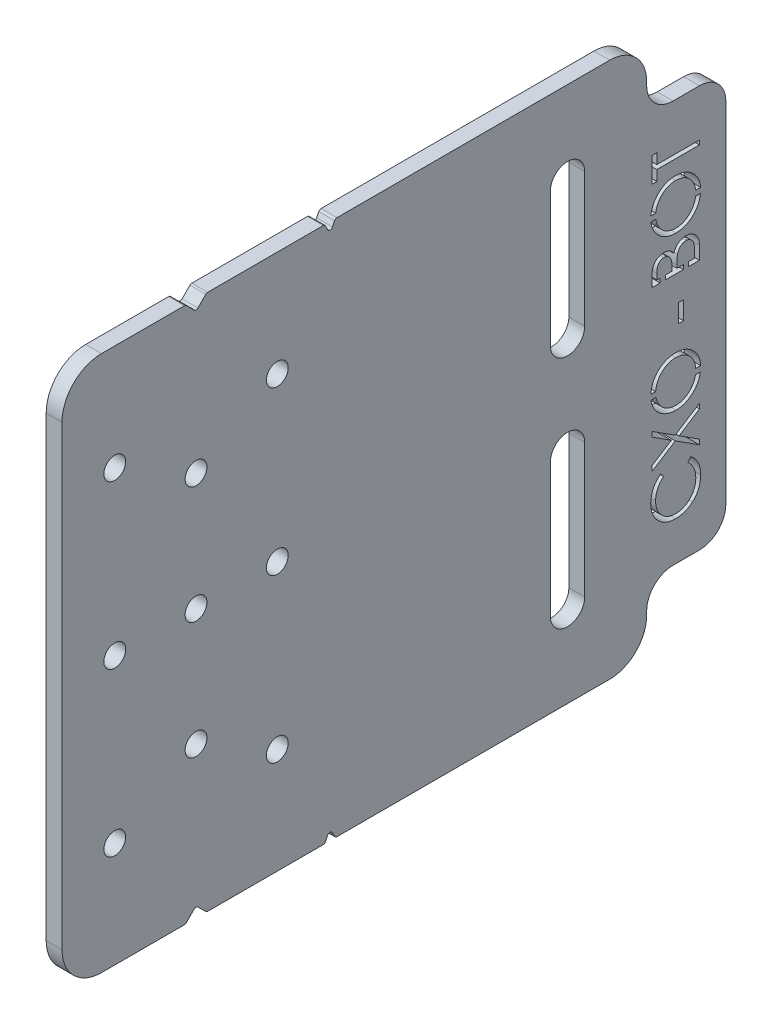
SolidWorks part; units mm, degrees
ref_plane "Front Plane" through (0, 0, 0) normal (0, 0, 1) x (1, 0, 0)
ref_plane "Top Plane" through (0, 0, 0) normal (0, 1, 0) x (1, 0, 0)
ref_plane "Right Plane" through (0, 0, 0) normal (1, 0, 0) x (0, 0, -1)
sketch "Sketch1" plane through (0, 0, 0) normal (1, 0, 0) x (0, 0, -1)
  line L0 (25.4, 60.8724) -> (25.4, -43.1362) construction
  line L1 (0, 55) -> (0, -55) construction
  line L2 (-25.4, 60.8724) -> (-25.4, -43.1362) construction
  line L3 (70.4, 39.6984) -> (70.4, -31.2158) construction
  line L4 (-25.4, 50.8) -> (25.4, 50.8)
  line L5 (-25.4, 50.8) -> (-25.4, -50.8)
  line L6 (-25.4, -50.8) -> (25.4, -50.8)
  line L7 (25.4, 50.8) -> (25.4, -50.8)
  line L8 (-25.4, 50.8) -> (25.4, -50.8) construction
  line L9 (-25.4, -50.8) -> (25.4, 50.8) construction
  line L10 (70.4, 34.925) -> (70.4, 9.525) construction
  line L11 (73.65, 34.925) -> (73.65, 9.525)
  line L12 (67.15, 34.925) -> (67.15, 9.525)
  line L13 (70.4, -9.525) -> (70.4, -34.925) construction
  line L14 (73.65, -9.525) -> (73.65, -34.925)
  line L15 (67.15, -9.525) -> (67.15, -34.925)
  line L16 (0, 22.225) -> (0, -22.225) construction
  line L17 (85.4, 58.462) -> (85.4, -44.2534) construction
  line L18 (55.4, 58.462) -> (55.4, -44.2534) construction
  line L19 (25.4, 50.8) -> (85.4, 50.8)
  line L20 (85.4, 50.8) -> (85.4, -50.8)
  line L21 (85.4, -50.8) -> (25.4, -50.8)
  line L22 (0, 0) -> (-25.4, 0) construction
  line L23 (-15.4, 30.8) -> (-15.4, 0) construction
  line L24 (-15.4, 15.4) -> (-25.4, 15.4) construction
  line L25 (-2, 50.8) -> (0, 48.8)
  line L26 (0, 48.8) -> (2, 50.8)
  line L27 (-2, -50.8) -> (0, -48.8)
  line L28 (0, -48.8) -> (2, -50.8)
  line L29 (24.4, 50.8) -> (25.4, 48.8)
  line L30 (25.4, 48.8) -> (26.4, 50.8)
  line L31 (24.4, -50.8) -> (25.4, -48.8)
  line L32 (25.4, -48.8) -> (26.4, -50.8)
  arc A0 (73.65, 34.925) -> (67.15, 34.925) centre (70.4, 34.925) ccw
  arc A1 (67.15, 9.525) -> (73.65, 9.525) centre (70.4, 9.525) ccw
  arc A2 (73.65, -9.525) -> (67.15, -9.525) centre (70.4, -9.525) ccw
  arc A3 (67.15, -34.925) -> (73.65, -34.925) centre (70.4, -34.925) ccw
  circle A4 centre (0, 22.225) radius 2.07
  circle A5 centre (0, -22.225) radius 2.07
  circle A7 centre (15.4, 30.8) radius 2.07
  circle A8 centre (15.4, -30.8) radius 2.07
  circle A9 centre (-15.4, -30.8) radius 2.07
  circle A10 centre (-15.4, 30.8) radius 2.07
  circle A11 centre (0, 0) radius 2.07
  circle A12 centre (15.4, 0) radius 2.07
  circle A13 centre (-15.4, 0) radius 2.07
  point P8 (0, 0)
  point P17 (70.4, 22.225)
  point P22 (70.4, -22.225)
  point P30 (0, 0)
  dimension "D10" = 4.14
  dimension "D12" = 2
  dimension "D1" = 25.4
  dimension "D2" = 50.8
  dimension "D3" = 30
  dimension "D4" = 6.5
  dimension "D5" = 25.4
  dimension "D6" = 50.8
  dimension "D7" = 101.6
  dimension "D8" = 19.05
  dimension "D9" = 15
  dimension "D11" = 10
  dimension "D13" = 1
extrude "Boss-Extrude1" add sketch "Sketch1" along normal mid plane 3 contours L21 L20 L19 L7 A3 L15 A2 L14 A1 L12 A0 L11 | L7 L4 L5 L6
fillet "Fillet1" radius 7.5 2 edges at (0, -50.8, 25.4) (0, 50.8, 25.4)
fillet "Fillet2" radius 0.5 12 edges at (0, -50.8, -24.4) (0, -48.8, -25.4) (0, -50.8, -26.4) (0, -50.8, 2) (0, -50.8, -2) (0, -48.8, 0) (0, 50.8, -24.4) (0, 50.8, -26.4) (0, 48.8, 0) (0, 48.8, -25.4) (0, 50.8, -2) (0, 50.8, 2)
fillet "Fillet3" radius 7 2 edges at (0, 50.8, -85.4) (0, -50.8, -85.4)
sketch "Sketch2" plane through (1.5, 0, 0) normal (1, 0, 0) x (0, 0, -1)
  line L0 (100.4, 38.1) -> (100.4, -38.1)
  line L1 (26.709, 50.8) -> (78.4, 50.8) construction
  line L2 (85.4, 43.8) -> (85.4, -43.8) construction
  line L3 (100.4, 38.1) -> (85.4, 38.1)
  line L4 (85.4, 38.1) -> (85.4, -38.1)
  line L5 (85.4, -38.1) -> (100.4, -38.1)
  point P3 (100.4, 0)
  dimension "D1" = 12.7
  dimension "D2" = 15
extrude "Boss-Extrude2" add sketch "Sketch2" against normal up to surface (3 mm away)
fillet "Fillet5" radius 5 4 edges at (0, -38.1, -85.4) (0, -38.1, -100.4) (0, 38.1, -100.4) (0, 38.1, -85.4)
sketch "Sketch3" plane through (1.5, 0, 0) normal (1, 0, 0) x (0, 0, -1)
  line L0 (95.4, -38.1) -> (95.4, 38.1) construction
  line L1 (100.4, -33.1) -> (100.4, 33.1) construction
  arc A0 (95.4, -38.1) -> (100.4, -33.1) centre (95.4, -33.1) ccw construction
  arc A1 (100.4, 33.1) -> (95.4, 38.1) centre (95.4, 33.1) ccw construction
  text T0 "CXO - BOT" font "Century Gothic" height 9
  dimension "D1" = 5
extrude "Cut-Extrude2" cut sketch "Sketch3" against normal blind 10
sketch "Sketch5" plane through (1.5, 0, 0) normal (1, 0, 0) x (0, 0, -1)
  line L0 (88.4527, 11.3585) -> (88.4527, 7.2648)
  line L1 (88.4527, 7.2648) -> (92.832, 7.2648)
  line L2 (92.832, 7.2648) -> (92.832, 11.8345)
  line L3 (83.4546, 20.8269) -> (97.8301, 20.8269)
  line L4 (84.0034, -8.4498) -> (97.472, -8.4498)
extrude "Extrude-Thin2" add sketch "Sketch5" against normal up to surface (3 mm away) thin up to face at (-1.5, 20.8756, -90.9077) thin type mid plane wall 1
